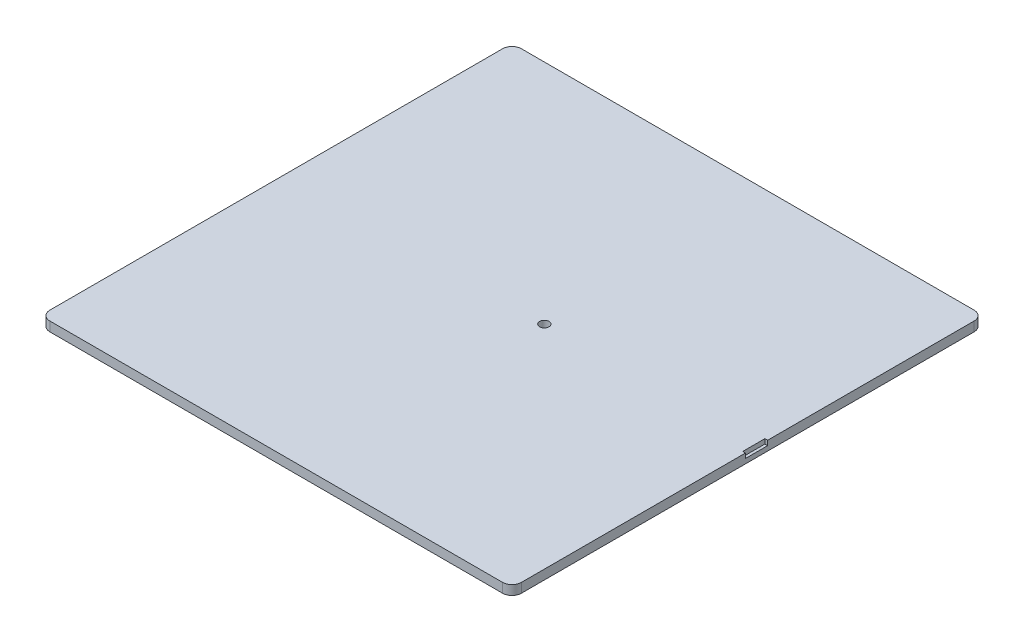
SolidWorks part; units mm, degrees
ref_plane "Front Plane" through (0, 0, 0) normal (0, 0, 1) x (1, 0, 0)
ref_plane "Top Plane" through (0, 0, 0) normal (0, 1, 0) x (1, 0, 0)
ref_plane "Right Plane" through (0, 0, 0) normal (1, 0, 0) x (0, 0, -1)
sketch "Sketch1" plane through (0, 0, 0) normal (0, 1, 0) x (1, 0, 0)
  line L1 (-240, -250) -> (240, -250)
  line L2 (-250, -240) -> (-250, 240)
  line L3 (-240, 250) -> (240, 250)
  line L4 (250, -240) -> (250, 240)
  line L5 (-250, -250) -> (250, 250) construction
  line L6 (-250, 250) -> (250, -250) construction
  arc A0 (-240, -250) -> (-250, -240) centre (-240, -240) cw
  arc A1 (240, -250) -> (250, -240) centre (240, -240) ccw
  arc A2 (240, 250) -> (250, 240) centre (240, 240) cw
  arc A3 (-250, 240) -> (-240, 250) centre (-240, 240) cw
  circle A4 centre (25.0333, 9.2919) radius 5
  point P0 (0, 0)
  dimension "D2" = 10
  dimension "D1" = 500
extrude "Boss-Extrude1" add sketch "Sketch1" along normal mid plane 10
sketch "Sketch4" plane through (250, 0, 0) normal (1, 0, 0) x (0, 0, -1)
  line L0 (-2.4581, 5) -> (-2.4581, 0.011)
  line L1 (-240, 5) -> (240, 5) construction
  line L2 (-2.4581, 0.011) -> (21.0419, 0.011)
  line L3 (21.0419, 0.011) -> (21.0419, 5)
  line L4 (21.0419, 5) -> (-2.4581, 5)
extrude "Cut-Extrude3" cut sketch "Sketch4" against normal blind 2.9
